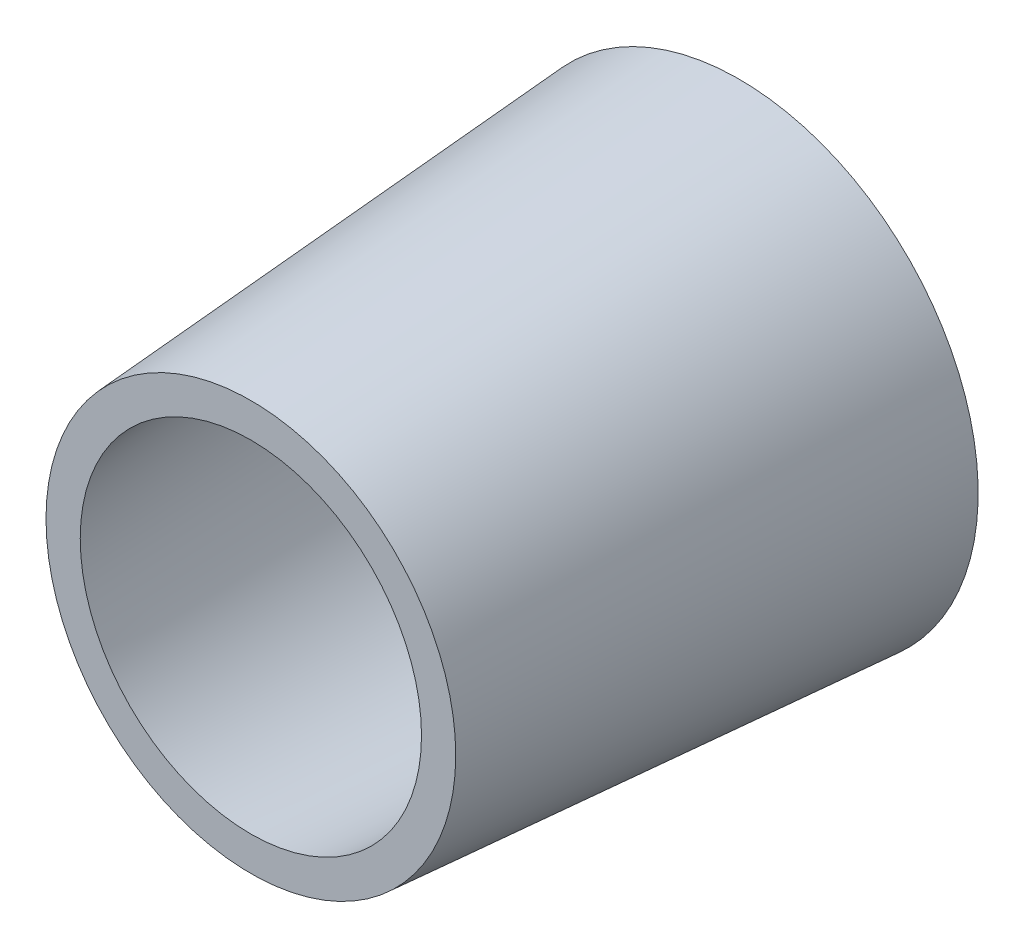
SolidWorks part; units mm, degrees
ref_plane "Front Plane" through (0, 0, 0) normal (1, 0, 0) x (0, 1, 0)
ref_plane "Top Plane" through (0, 0, 0) normal (0, 0, 1) x (0, 1, 0)
ref_plane "Right Plane" through (0, 0, 0) normal (0, 1, 0) x (-1, 0, 0)
sketch "Sketch1" plane through (0, 0, 0) normal (1, 0, 0) x (0, 1, 0)
  line L0 (0, 0) -> (0, 36.3237)
  line L1 (0, 36.3237) -> (15.24, 36.3237)
  line L2 (15.24, 36.3237) -> (17.78, 0)
  line L3 (17.78, 0) -> (0, 0)
  dimension "D1" = 4
  dimension "D2" = 17.78
  dimension "D3" = 15.24
revolve "Revolve1" add sketch "Sketch1" angle 360 about L0
shell "Shell2" thickness 2.54
